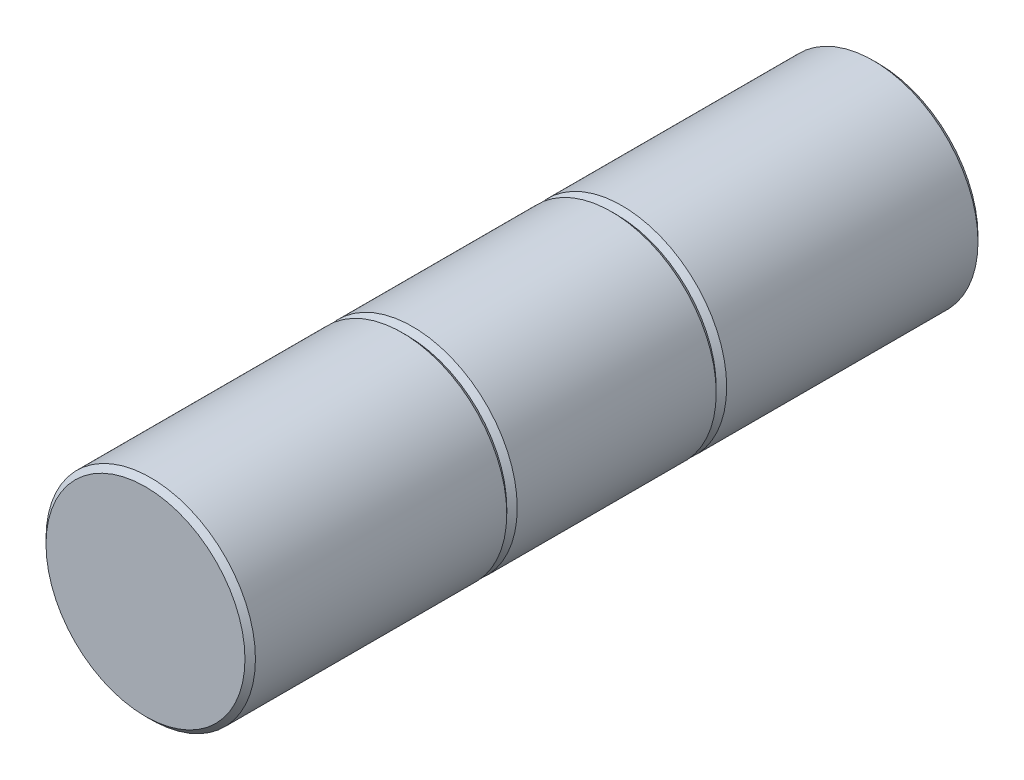
SolidWorks part; units mm, degrees
ref_plane "Front Plane" through (0, 0, 0) normal (0, 0, 1) x (1, 0, 0)
ref_plane "Top Plane" through (0, 0, 0) normal (0, 1, 0) x (1, 0, 0)
ref_plane "Right Plane" through (0, 0, 0) normal (1, 0, 0) x (0, 0, -1)
sketch "Sketch2" plane through (0, 0, 0) normal (0, 0, 1) x (1, 0, 0)
  circle A0 centre (0, 0) radius 2
  dimension "D1" = 4
extrude "Boss-Extrude1" add sketch "Sketch2" along normal mid plane 4
sketch "Sketch3" plane through (0, 0, 2) normal (0, 0, 1) x (1, 0, 0)
  circle A1 centre (0, 0) radius 2
  circle A2 centre (0, 0) radius 2
  dimension "D1" = 0
extrude "Boss-Extrude2" add sketch "Sketch3" along normal blind 5 separate body
sketch "Sketch4" plane through (0, 0, -2) normal (0, 0, -1) x (-1, 0, 0)
  circle A1 centre (0, 0) radius 2
  circle A2 centre (0, 0) radius 2
  dimension "D1" = 0
extrude "Boss-Extrude3" add sketch "Sketch4" along normal blind 5 separate body
chamfer "Chamfer1" distance 0.1 angle 45 2 edges at (2, 0, 2) (2, 0, 7)
chamfer "Chamfer2" distance 0.1 angle 45 2 edges at (-2, 0, -2) (-2, 0, -7)
chamfer "Chamfer3" distance 0.1 angle 45 2 edges at (2, 0, -2) (2, 0, 2)
